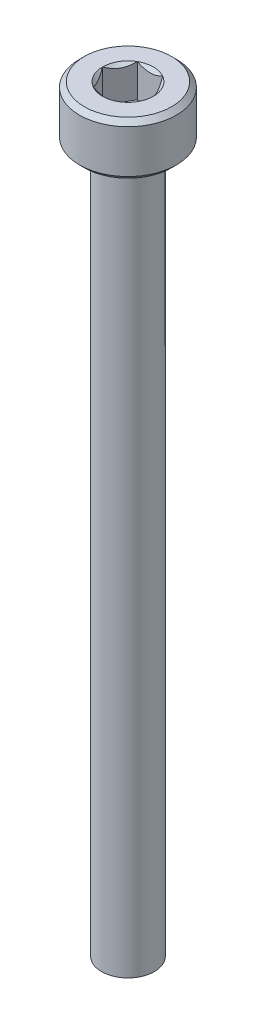
SolidWorks part; units mm, degrees
ref_plane "Front" through (0, 0, 0) normal (0, 0, 1) x (1, 0, 0)
ref_plane "Top" through (0, 0, 0) normal (0, 1, 0) x (1, 0, 0)
ref_plane "Right" through (0, 0, 0) normal (1, 0, 0) x (0, 0, -1)
sketch "Sketch1" plane through (0, 0, 0) normal (0, 1, 0) x (1, 0, 0)
  circle A0 centre (0, 0) radius 2.75
  dimension "D1" = 5.5
extrude "Boss-Extrude1" add sketch "Sketch1" along normal blind 3
sketch "Sketch2" plane through (0, 3, 0) normal (0, 1, 0) x (1, 0, 0)
  line L1 (0.7217, 1.25) -> (-0.7217, 1.25)
  line L2 (-0.7217, 1.25) -> (-1.4434, 0)
  line L3 (-1.4434, 0) -> (-0.7217, -1.25)
  line L4 (-0.7217, -1.25) -> (0.7217, -1.25)
  line L5 (0.7217, -1.25) -> (1.4434, 0)
  line L6 (1.4434, 0) -> (0.7217, 1.25)
  circle A0 centre (0, 0) radius 1.25 construction
  point P10 (0, 1.25)
  dimension "D1" = 2.5
extrude "Cut-Extrude1" cut sketch "Sketch2" against normal blind 1.88
sketch "Sketch5" plane through (0, 3, 0) normal (0, 1, 0) x (1, 0, 0)
  circle A0 centre (0, 0) radius 1.4434
extrude "Cut-Extrude2" cut sketch "Sketch5" against normal through all draft 45
chamfer "Chamfer1" distance 0.275 angle 45 2 edges at (0, 0, 2.75) (0, 3, 2.75)
sketch "草图1" plane through (0, 0, 0) normal (0, -1, 0) x (-1, 0, 0)
  circle A0 centre (0, 0) radius 1.5
  dimension "D1" = 3
extrude "凸台-拉伸1" add sketch "草图1" along normal blind 40
